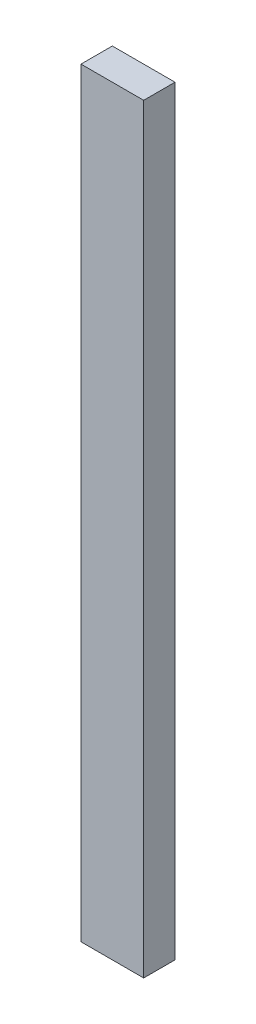
SolidWorks part; units mm, degrees
material "Sapin"
ref_plane "Plan de face" through (0, 0, 0) normal (0, 0, 1) x (1, 0, 0)
ref_plane "Plan de dessus" through (0, 0, 0) normal (0, 1, 0) x (1, 0, 0)
ref_plane "Plan de droite" through (0, 0, 0) normal (1, 0, 0) x (0, 0, -1)
sketch "Esquisse1" plane through (0, 0, 0) normal (0, 0, 1) x (1, 0, 0)
  line L1 (-24, -291) -> (24, -291)
  line L2 (-24, -291) -> (-24, 291)
  line L3 (-24, 291) -> (24, 291)
  line L4 (24, -291) -> (24, 291)
  line L5 (-24, -291) -> (24, 291) construction
  line L6 (-24, 291) -> (24, -291) construction
  point P0 (0, 0)
  dimension "D1" = 582
  dimension "D2" = 48
extrude "Boss.-Extru.1" add sketch "Esquisse1" along normal mid plane 24
sketch "Esquisse2" plane through (24, 0, 0) normal (1, 0, 0) x (0, 0, -1)
  line L0 (-12, -291) -> (12, -291) construction
  line L1 (-12, -291) -> (-12, 291) construction
  circle A0 centre (0, -281) radius 4.5
  dimension "D1" = 9
  dimension "D2" = 10
  dimension "D3" = 12
extrude "Enlèv. mat.-Extru.1" [suppressed] cut sketch "Esquisse2" against normal through all
